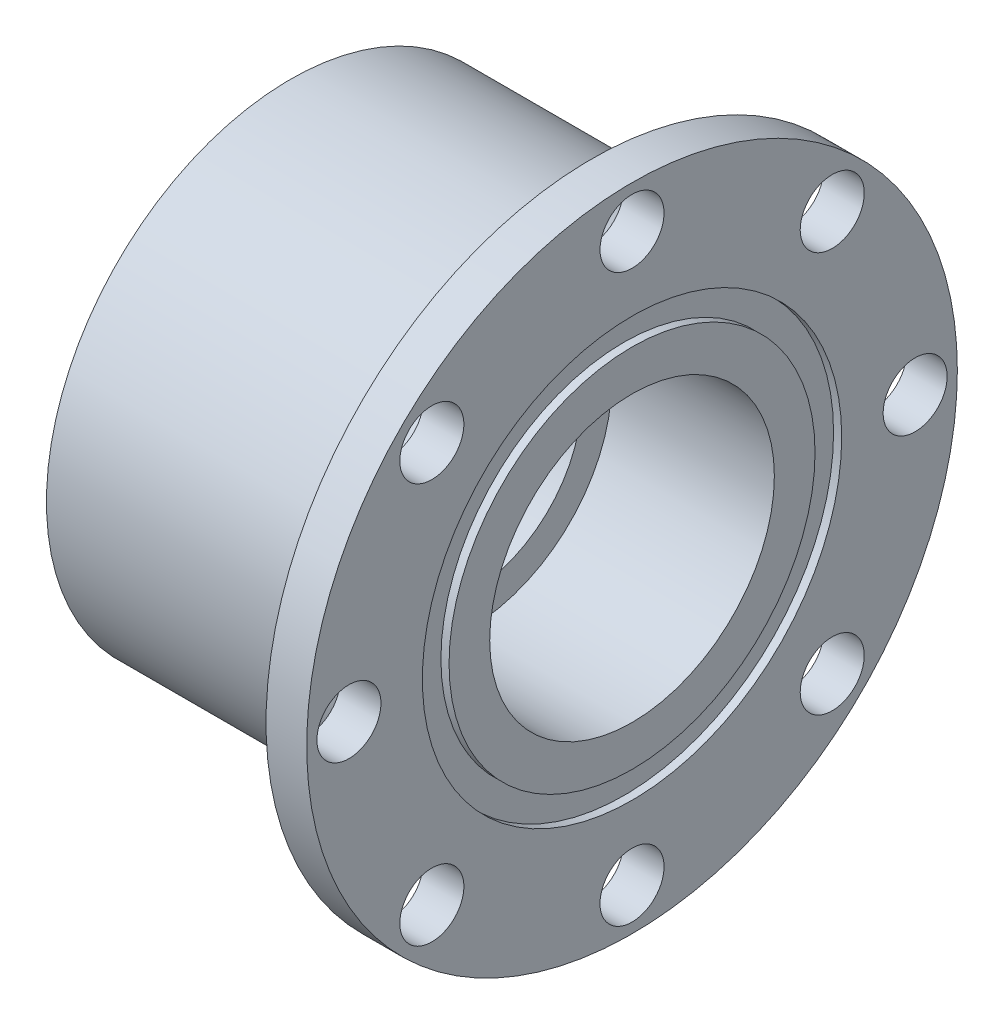
SolidWorks part; units mm, degrees
ref_plane "Front Plane" through (0, 0, 0) normal (0, 0, 1) x (1, 0, 0)
ref_plane "Top Plane" through (0, 0, 0) normal (0, 1, 0) x (1, 0, 0)
ref_plane "Right Plane" through (0, 0, 0) normal (1, 0, 0) x (0, 0, -1)
sketch "Sketch1" plane through (0, 0, 0) normal (1, 0, 0) x (0, 0, -1)
  circle A0 centre (0, 0) radius 38.1
  dimension "D1" = 76.2
extrude "main body" add sketch "Sketch1" along normal blind 27.94
sketch "Sketch2" plane through (27.94, 0, 0) normal (1, 0, 0) x (0, 0, -1)
  circle A0 centre (0, 0) radius 17.5
  dimension "D1" = 35
extrude "Static Seal Hole" cut sketch "Sketch2" against normal blind 10.25
sketch "Sketch3" plane through (17.69, 0, 0) normal (1, 0, 0) x (0, 0, -1)
  point P0 (0, 0)
hole_wizard "Shaft hole" positions "Sketch3" profile "Sketch5" hole size "Ø18.0" standard "ANSI Metric" end condition through all
sketch "Sketch5" plane through (17.69, 0, 0) normal (0, 1, 0) x (0, 0, -1)
  line L0 (0, 0) -> (0, 17.69)
  line L1 (0, 17.69) -> (9, 17.69)
  line L2 (9, 17.69) -> (9, 0)
  line L5 (9, 0) -> (0, 0)
  line L11 (0, -6.35) -> (0, 107.95) construction
  dimension "Thru Hole Dia." = 18
  dimension "Thru Hole Depth" = 17.69
sketch "Sketch14" plane through (27.94, 0, 0) normal (1, 0, 0) x (0, 0, -1)
  circle A0 centre (0, 0) radius 22.225
  circle A1 centre (0, 0) radius 38.1 construction
  circle A2 centre (0, 0) radius 38.1
  dimension "D1" = 44.45
extrude "rotating seal space" add sketch "Sketch14" along normal blind 25.4
sketch "Sketch7" plane through (53.34, 0, 0) normal (1, 0, 0) x (0, 0, -1)
  circle A0 centre (0, 0) radius 50.8
  circle A3 centre (0, 0) radius 22.225 construction
  circle A4 centre (0, 0) radius 22.225
  dimension "D1" = 101.6
extrude "face joint" add sketch "Sketch7" against normal blind 6.35
sketch "Sketch8" plane through (0, 0, 0) normal (-1, 0, 0) x (0, 0, 1)
  circle A0 centre (0, 0) radius 20
  dimension "D1" = 40
extrude "bearing hole" cut sketch "Sketch8" against normal blind 13
sketch "Sketch12" plane through (46.99, 0, 0) normal (-1, 0, 0) x (0, 0, 1)
  point P0 (-44.2067, 0)
  point P4 (-31.2588, 31.2588)
  point P5 (0, 44.2067)
  point P6 (31.2588, 31.2588)
  point P7 (44.2067, 0)
  point P8 (31.2588, -31.2588)
  point P9 (0, -44.2067)
  point P10 (-31.2588, -31.2588)
  point P11 (0, 0)
  dimension "D1" = 8
hole_wizard "Screw holes" positions "Sketch12" profile "Sketch13" hole size "M8" standard "ANSI Metric" end condition through all
sketch "Sketch13" plane through (46.99, 0, -44.2067) normal (0, 1, 0) x (0, 0, 1)
  line L0 (0, 0) -> (0, 6.35)
  line L1 (0, 6.35) -> (5, 6.35)
  line L2 (5, 6.35) -> (5, 0)
  line L5 (5, 0) -> (0, 0)
  line L11 (0, -6.35) -> (0, 107.95) construction
  dimension "Thru Hole Dia." = 10
  dimension "Thru Hole Depth" = 6.35
sketch "Sketch16" plane through (53.34, 0, 0) normal (1, 0, 0) x (0, 0, -1)
  circle A0 centre (0, 0) radius 32.7406
  circle A1 centre (0, 0) radius 28.575
  dimension "D1" = 4.1656
  dimension "D2" = 57.15
extrude "Gasket ring" cut sketch "Sketch16" against normal blind 1.27
